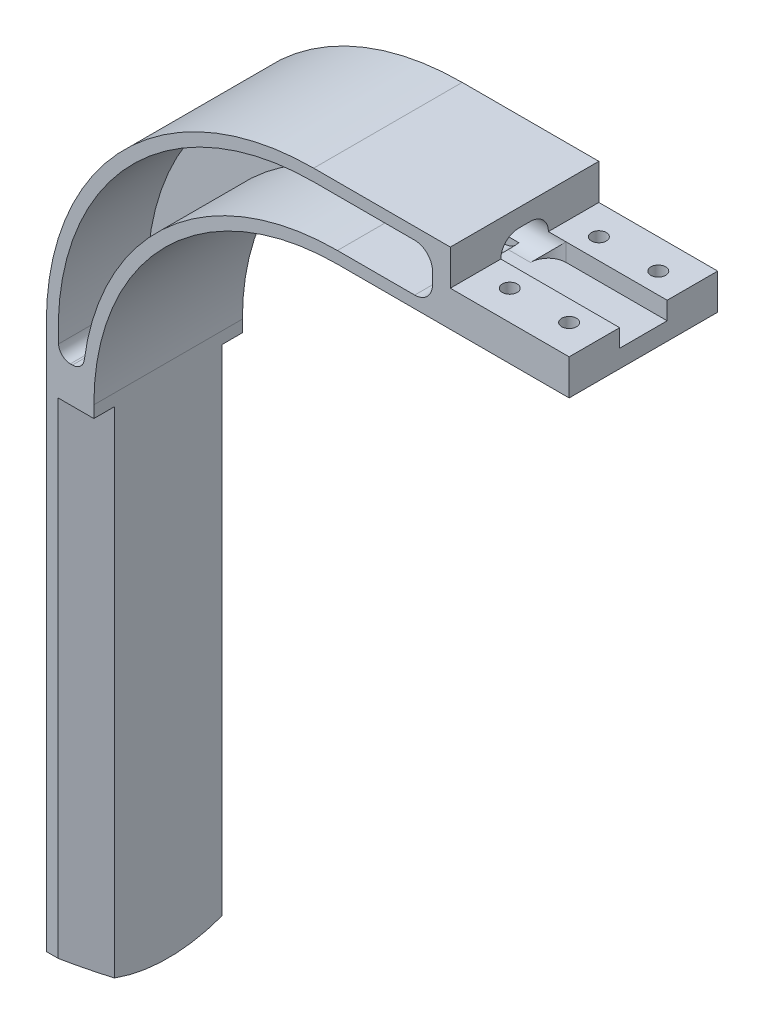
SolidWorks part; units mm, degrees
material "Сплав 2024"
ref_plane "Спереди" through (0, 0, 0) normal (0, 0, 1) x (1, 0, 0)
ref_plane "Сверху" through (0, 0, 0) normal (0, 1, 0) x (1, 0, 0)
ref_plane "Справа" through (0, 0, 0) normal (1, 0, 0) x (0, 0, -1)
sketch "Эскиз1" plane through (0, 0, 0) normal (0, 0, 1) x (1, 0, 0)
  line L0 (0, 0) -> (0, 95)
  line L1 (0, 0) -> (8, 0)
  line L2 (-20.7345, 140) -> (144.5665, 140) construction
  line L3 (88, 163.3115) -> (88, 122.0175) construction
  line L4 (8, 0) -> (8, 87)
  line L6 (88, 140) -> (45, 140)
  line L7 (88, 140) -> (88, 128)
  line L8 (88, 128) -> (49, 128)
  arc A0 (49, 128) -> (8, 87) centre (49, 87) ccw
  arc A1 (45, 140) -> (0, 95) centre (45, 95) ccw
  dimension "D1" = 95
  dimension "D2" = 87
  dimension "D3" = 140
  dimension "D4" = 88
  dimension "D5" = 8
  dimension "D6" = 12
extrude "Бобышка-Вытянуть1" add sketch "Эскиз1" along normal blind 25
sketch "Эскиз2" plane through (0, 0, 25) normal (0, 0, 1) x (1, 0, 0)
  line L1 (88, 140) -> (68, 140)
  line L2 (88, 140) -> (88, 134)
  line L3 (88, 134) -> (68, 134)
  line L4 (68, 140) -> (68, 134)
  dimension "D1" = 20
  dimension "D2" = 6
extrude "Вырез-Вытянуть1" cut sketch "Эскиз2" against normal through all
sketch "Эскиз5" plane through (0, 0, 0) normal (0, -1, 0) x (1, 0, 0)
  line L0 (8, 3.4641) -> (2, 0)
  line L1 (8, 25) -> (8, 0) construction
  line L2 (8, 3.4641) -> (10.1941, 4.7308)
  line L3 (2, 0) -> (8, 0)
  line L4 (8, 0) -> (8, 3.4641) construction
  line L5 (0, 25) -> (0, 0) construction
  line L6 (8, 12.5) -> (7.5, 12.5) construction
  line L7 (8, 25) -> (8, 0) construction
  line L8 (8, 25) -> (8, 21.5359) construction
  line L9 (2, 25) -> (8, 25)
  line L10 (8, 21.5359) -> (2, 25)
  line L11 (0, 0) -> (8, 0) construction
  line L12 (10.1941, 4.7308) -> (10.1941, 0)
  line L13 (8, 0) -> (49, 0) construction
  line L14 (10.1941, 0) -> (8, 0)
  line L15 (8, 21.5359) -> (10.1941, 20.2692)
  line L16 (10.1941, 20.2692) -> (10.1941, 25)
  line L17 (49, 25) -> (8, 25) construction
  line L18 (10.1941, 25) -> (8, 25)
  dimension "D1" = 2
  dimension "D2" = 60
extrude "Вырез-Вытянуть2" cut sketch "Эскиз5" against normal blind 85
sketch "Эскиз6" plane through (0, 0, 0) normal (-1, 0, 0) x (0, 0, 1)
  line L0 (12.5, 0) -> (12.5, 16.6862) construction
  line L1 (25, 0) -> (0, 0) construction
  line L2 (12.5, -11.9161) -> (12.5, 92.5) construction
  line L3 (10, -11.9161) -> (10, 92.5)
  line L4 (15, -11.9161) -> (15, 92.5)
  line L5 (25, 95) -> (0, 95) construction
  arc A0 (10, -11.9161) -> (15, -11.9161) centre (12.5, -11.9161) ccw
  arc A1 (15, 92.5) -> (10, 92.5) centre (12.5, 92.5) ccw
  point P7 (12.5, 40.292)
  dimension "D1" = 5
extrude "Вырез-Вытянуть4" cut sketch "Эскиз6" against normal blind 5
sketch "Эскиз3" plane through (0, 0, 25) normal (0, 0, -1) x (-1, 0, 0)
  line L0 (-65, 138) -> (-65, 130)
  line L2 (-6.1865, 91) -> (-2.1865, 91)
  line L3 (-45, 138) -> (-65, 138)
  line L4 (-68, 140) -> (-68, 134) construction
  line L5 (-65, 130) -> (-49, 130)
  arc A4 (-45, 138) -> (-2.1865, 91) centre (-45, 95) cw
  arc A5 (-49, 130) -> (-6.1865, 91) centre (-49, 87) cw
  arc A6 (0, 95) -> (-45, 140) centre (-45, 95) ccw construction
  arc A7 (-8, 87) -> (-49, 128) centre (-49, 87) ccw construction
  dimension "D1" = 2
  dimension "D2" = 2
  dimension "D3" = 3
  dimension "D4" = 4
extrude "Вырез-Вытянуть3" cut sketch "Эскиз3" along normal up to surface (15 mm away) up to face at (2.5, 46.25, 10)
fillet "Скругление3" radius 2 2 edges at (6.1865, 91, 17.5) (2.1865, 91, 20)
fillet "Скругление4" radius 3 2 edges at (65, 138, 17.5) (65, 130, 17.5)
ref_plane "Плоскость1" through (0, 10, 0) normal (0, 1, 0) x (1, 0, 0)
sketch "Эскиз8" plane through (0, 10, 0) normal (0, 1, 0) x (1, 0, 0)
  line L0 (0, -2) -> (1.5, -2)
  line L1 (0, -12.5) -> (0, 0) construction
  line L2 (1.5, -2) -> (1.5, -3)
  line L3 (3.5, -4) -> (5.5, -4)
  line L4 (5.5, -4) -> (5.5, -8)
  line L5 (5.5, -8) -> (0, -8)
  line L6 (0, -8) -> (0, -2)
  line L7 (45, 0) -> (0, 0) construction
  line L8 (2.0727, -10) -> (0, -10) construction
  line L9 (1.5, -3) -> (3.5, -3)
  line L10 (3.5, -3) -> (3.5, -4)
  line L11 (8, -25) -> (8, 0) construction
  line L12 (8, -12.5) -> (6.1534, -12.5) construction
  line L13 (3.5, -22) -> (3.5, -21)
  line L14 (1.5, -22) -> (3.5, -22)
  line L15 (0, -17) -> (0, -23)
  line L16 (5.5, -17) -> (0, -17)
  line L17 (5.5, -21) -> (5.5, -17)
  line L18 (3.5, -21) -> (5.5, -21)
  line L19 (1.5, -23) -> (1.5, -22)
  line L20 (0, -23) -> (1.5, -23)
  dimension "D1" = 2
  dimension "D2" = 2
  dimension "D3" = 4
  dimension "D4" = 1
  dimension "D5" = 1.5
  dimension "D6" = 2
  dimension "D7" = 2.5
extrude "Вырез-Вытянуть6" cut sketch "Эскиз8" along normal blind 75
sketch "Эскиз9" plane through (0, 134, 0) normal (0, 1, 0) x (1, 0, 0)
  line L0 (88, 0) -> (68, -25) construction
  line L1 (88, 0) -> (88, -25) construction
  line L2 (73, -5) -> (83, -5) construction
  line L3 (73, -5) -> (73, -20) construction
  line L4 (73, -20) -> (83, -20) construction
  line L5 (83, -5) -> (83, -20) construction
  line L6 (73, -5) -> (83, -20) construction
  line L7 (73, -20) -> (83, -5) construction
  line L8 (68, 0) -> (88, 0) construction
  point P4 (78, -12.5)
  dimension "D1" = 5
  dimension "D2" = 5
hole_wizard "Отверстие обработанное метчиком M3x0.51" positions "Эскиз11" profile "Эскиз10" tap size "M3x0.5" standard "Ansi Metric" end condition up to next
sketch "Эскиз11" plane through (19.192, 134, 18.7997) normal (0, 1, 0) x (1, 0, 0)
  point P0 (53.808, 13.7997)
  point P3 (63.808, 13.7997)
  point P6 (63.808, -1.2003)
  point P9 (53.808, -1.2003)
cosmetic thread "Отверстие резьбы2" parameters "D2"=3
cosmetic thread "Отверстие резьбы3" parameters "D2"=3
cosmetic thread "Отверстие резьбы4" parameters "D2"=3
cosmetic thread "Отверстие резьбы5" parameters "D2"=3
sketch "Эскиз10" plane through (73, 134, 5) normal (1, 0, 0) x (0, 0, 1)
  line L0 (0, 0) -> (0, 6)
  line L1 (0, 6) -> (1.25, 6)
  line L2 (1.25, 6) -> (1.25, 0)
  line L5 (1.25, 0) -> (0, 0)
  line L11 (0, -6.35) -> (0, 107.95) construction
  dimension "Диаметр проходного сверла" = 2.5
  dimension "Глубина проходного сверла" = 6
sketch "Эскиз12" plane through (0, 0, 0) normal (-1, 0, 0) x (0, 0, 1)
  line L0 (12.5, 0) -> (12.5, 6.3491) construction
  line L1 (10, 0) -> (15, 0) construction
  line L3 (0, 3.302) -> (0, 0)
  line L4 (0, 95) -> (0, 0) construction
  line L5 (0, 0) -> (12.5, 0)
  line L6 (12.5, 0) -> (25, 0)
  line L7 (25, 0) -> (25, 3.302)
  line L8 (25, 95) -> (25, 0) construction
  arc A0 (0, 3.302) -> (25, 3.302) centre (12.5, 26.1) ccw
  dimension "D1" = 52
  dimension "D2" = 26.1
extrude "Вырез-Вытянуть7" cut sketch "Эскиз12" against normal up to next
sketch "Эскиз13" plane through (0, 134, 0) normal (0, 1, 0) x (1, 0, 0)
  line L0 (88, -12.5) -> (68, -12.5) construction
  line L1 (88, 0) -> (88, -25) construction
  line L2 (68, 0) -> (68, -25) construction
  line L4 (68, -8.5) -> (88, -8.5)
  line L5 (68, -8.5) -> (68, -16.5)
  line L6 (68, -16.5) -> (88, -16.5)
  line L7 (88, -8.5) -> (88, -16.5)
  line L8 (68, -8.5) -> (88, -16.5) construction
  line L9 (68, -16.5) -> (88, -8.5) construction
  point P6 (78, -12.5)
  dimension "D1" = 8
extrude "Вырез-Вытянуть8" cut sketch "Эскиз13" against normal blind 3
fillet "Скругление8" radius 3 2 edges at (68, 132.5, 8.5) (68, 132.5, 16.5)
sketch "Эскиз14" plane through (88, 0, 0) normal (1, 0, 0) x (0, 0, -1)
  line L0 (-12.5, 131) -> (-12.5, 154.1514) construction
  line L1 (-16.5, 131) -> (-8.5, 131) construction
  line L4 (-13.5, 134) -> (-11.5, 134) construction
  line L5 (-13.5, 137) -> (-11.5, 137)
  line L6 (-13.5, 131) -> (-11.5, 131)
  line L7 (-16.5, 131) -> (-16.5, 134) construction
  arc A0 (-13.5, 137) -> (-13.5, 131) centre (-13.5, 134) ccw
  arc A1 (-11.5, 131) -> (-11.5, 137) centre (-11.5, 134) ccw
  point P5 (-12.5, 134)
  dimension "D1" = 6
extrude "Вырез-Вытянуть9" cut sketch "Эскиз14" against normal blind 28
sketch "Эскиз15" plane through (0, 0, 0) normal (-1, 0, 0) x (0, 0, 1)
  line L0 (12.5, 92.5) -> (12.5, 85.5) construction
  line L1 (15, 92.5) -> (15, 85.5)
  line L2 (10, 92.5) -> (10, 85.5)
  line L3 (15, 0.2205) -> (15, 91.0916) construction
  arc A0 (15, 92.5) -> (10, 92.5) centre (12.5, 92.5) ccw
  arc A1 (10, 85.5) -> (15, 85.5) centre (12.5, 85.5) ccw
  point P3 (12.5, 89)
  dimension "D1" = 7
extrude "Вырез-Вытянуть10" cut sketch "Эскиз15" against normal blind 6
sketch "Эскиз19" plane through (0, 0, 0) normal (-1, 0, 0) x (0, 0, 1)
  line L0 (10, 85.5) -> (10, 0.2205) construction
  line L1 (15, 92.5) -> (15, 0.2205) construction
  line L2 (10, 10.1) -> (10, 0.2205)
  line L3 (15, 10.1) -> (15, 0.2205)
  line L4 (10, 10.1) -> (15, 10.1)
  arc A0 (10, 0.2205) -> (15, 0.2205) centre (12.5, 26.1) ccw construction
  arc A1 (10, 0.2205) -> (15, 0.2205) centre (12.5, 26.1) ccw
  dimension "D1" = 16
extrude "Бобышка-Вытянуть2" add sketch "Эскиз19" against normal up to surface (5 mm away) up to face at (5, 42.2051, 12.5)
sketch "Эскиз16" plane through (0, 0, 0) normal (-1, 0, 0) x (0, 0, 1)
  line L0 (25, 5.1) -> (0, 5.1) construction
  line L1 (25, 95) -> (25, 3.302) construction
  line L3 (0, 95) -> (0, 3.302) construction
  arc A0 (0, 3.302) -> (25, 3.302) centre (12.5, 26.1) ccw construction
  point P4 (12.5, 0.1)
  dimension "D1" = 5
hole_wizard "Отверстие обработанное метчиком M3x0.52" positions "Эскиз18" profile "Эскиз17" tap size "M3x0.5" standard "Ansi Metric"
sketch "Эскиз18" plane through (0, 0, 0) normal (-1, 0, 0) x (0, 0, 1)
  line L1 (25, 5.1) -> (0, 5.1) construction
  point P5 (12.5, 5.1)
sketch "Эскиз17" plane through (0, 5.1, 12.5) normal (0, 1, 0) x (0, 0, 1)
  line L0 (0, 0) -> (0, 4.7511)
  line L1 (0, 4.7511) -> (1.25, 4)
  line L2 (1.25, 4) -> (1.25, 0)
  line L5 (1.25, 0) -> (0, 0)
  line L10 (0, 4.7511) -> (-1.25, 4) construction
  line L11 (0, -6.35) -> (0, 107.95) construction
  dimension "Диаметр сверла" = 2.5
  dimension "Глубина сверла" = 4
  dimension "Угол заточки сверла" = 118
cosmetic thread "Отверстие резьбы1" parameters "D1"=4, "D2"=3
equation "\"D4@Эскиз1\" = 83 + 5"
equation "\"D3@Эскиз1\"=150.00-10"
